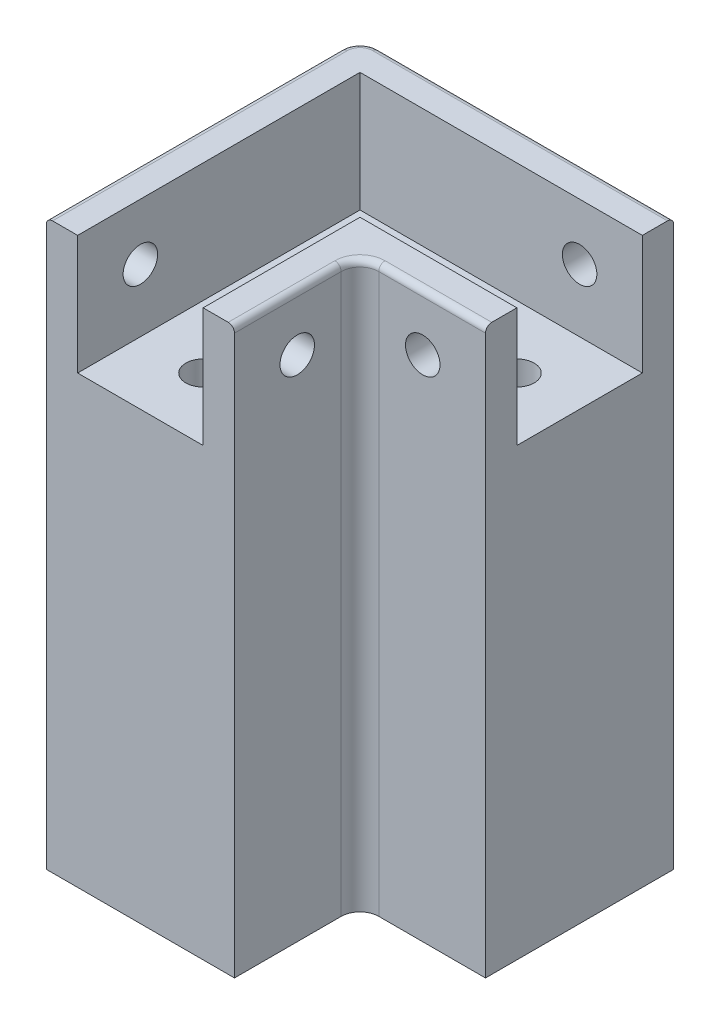
SolidWorks part; units mm, degrees
ref_plane "Front Plane" through (0, 0, 0) normal (0, 0, 1) x (1, 0, 0)
ref_plane "Top Plane" through (0, 0, 0) normal (0, 1, 0) x (1, 0, 0)
ref_plane "Right Plane" through (0, 0, 0) normal (1, 0, 0) x (0, 0, -1)
sketch "Sketch1" plane through (0, 0, 0) normal (0, 1, 0) x (1, 0, 0)
  line L1 (0, 0) -> (50, 0)
  line L2 (0, 0) -> (0, 50)
  line L3 (0, 50) -> (50, 50)
  line L4 (50, 0) -> (50, 50)
  dimension "D1" = 50
  dimension "D2" = 50
extrude "Boss-Extrude1" add sketch "Sketch1" along normal blind 90
sketch "Sketch2" plane through (0, 90, 0) normal (0, 1, 0) x (1, 0, 0)
  line L0 (0, 0) -> (50, 0) construction
  line L1 (5, 0) -> (25, 0)
  line L2 (5, 0) -> (5, 45)
  line L4 (25, 0) -> (25, 25)
  line L5 (0, 50) -> (0, 0) construction
  line L6 (50, 50) -> (0, 50) construction
  line L7 (50, 0) -> (50, 50) construction
  line L8 (5, 45) -> (50, 45)
  line L10 (25, 25) -> (50, 25)
  line L11 (50, 45) -> (50, 25)
  dimension "D1" = 20
  dimension "D2" = 5
  dimension "D3" = 5
  dimension "D4" = 20
extrude "Cut-Extrude1" cut sketch "Sketch2" against normal blind 19
sketch "Sketch3" plane through (0, 90, 0) normal (0, 1, 0) x (1, 0, 0)
  line L0 (25, 25) -> (50, 25) construction
  line L1 (50, 0) -> (29.9967, 0)
  line L2 (50, 0) -> (50, 20)
  line L3 (50, 20) -> (29.9967, 20)
  line L4 (29.9967, 0) -> (29.9967, 20)
  line L5 (25, 0) -> (25, 25) construction
  dimension "D1" = 5
  dimension "D2" = 4.9967
extrude "Cut-Extrude2" cut sketch "Sketch3" against normal through all
sketch "Sketch4" plane through (0, 0, 0) normal (0, -1, 0) x (1, 0, 0)
  line L0 (14.9984, 0) -> (14.9984, -50) construction
  line L1 (0, 0) -> (29.9967, 0) construction
  line L2 (50, -50) -> (0, -50) construction
  line L3 (50, -35) -> (0, -35) construction
  line L4 (50, -20) -> (50, -50) construction
  line L5 (0, -50) -> (0, 0) construction
  circle A0 centre (14.9984, -10) radius 6
  circle A1 centre (40, -35) radius 6
  circle A2 centre (14.9984, -35) radius 6
  dimension "D1" = 12
  dimension "D3" = 12
  dimension "D2" = 10
  dimension "D4" = 10
extrude "Cut-Extrude3" cut sketch "Sketch4" against normal offset from surface (66 mm away) 5 up to face at (26.6667, 71, -23.3333)
sketch "Sketch6" plane through (0, 66, 0) normal (0, -1, 0) x (1, 0, 0)
  circle A0 centre (14.9984, -10) radius 2.75
  circle A1 centre (40, -35) radius 2.75
  circle A3 centre (14.9984, -35) radius 2.75
  dimension "D1" = 5.5
  dimension "5" = 5.5
extrude "Cut-Extrude4" cut sketch "Sketch6" against normal through all
sketch "Sketch7" plane through (0, 0, 0) normal (-1, 0, 0) x (0, 0, 1)
  line L0 (-50, 90) -> (0, 90) construction
  line L1 (0, 90) -> (0, 0) construction
  circle A0 centre (-10, 81) radius 2.75
  dimension "D3" = 5.5
  dimension "D1" = 9
  dimension "D2" = 10
extrude "Cut-Extrude5" cut sketch "Sketch7" against normal through all
sketch "Sketch8" plane through (0, 0, -50) normal (0, 0, -1) x (-1, 0, 0)
  line L0 (-50, 90) -> (0, 90) construction
  line L1 (-50, 90) -> (-50, 0) construction
  circle A0 centre (-40, 81) radius 2.75
  dimension "D1" = 5.5
  dimension "D2" = 9
  dimension "D3" = 10
extrude "Cut-Extrude6" cut sketch "Sketch8" against normal through all
fillet "Fillet1" radius 3 2 edges at (29.9967, 45, -20) (0, 45, -50)
fillet "Fillet2" radius 1 6 edges at (26.5, 90, -50) (0.8787, 90, -49.1213) (0, 90, -23.5) (41.4984, 90, -20) (30.8754, 90, -19.1213) (29.9967, 90, -8.5)
